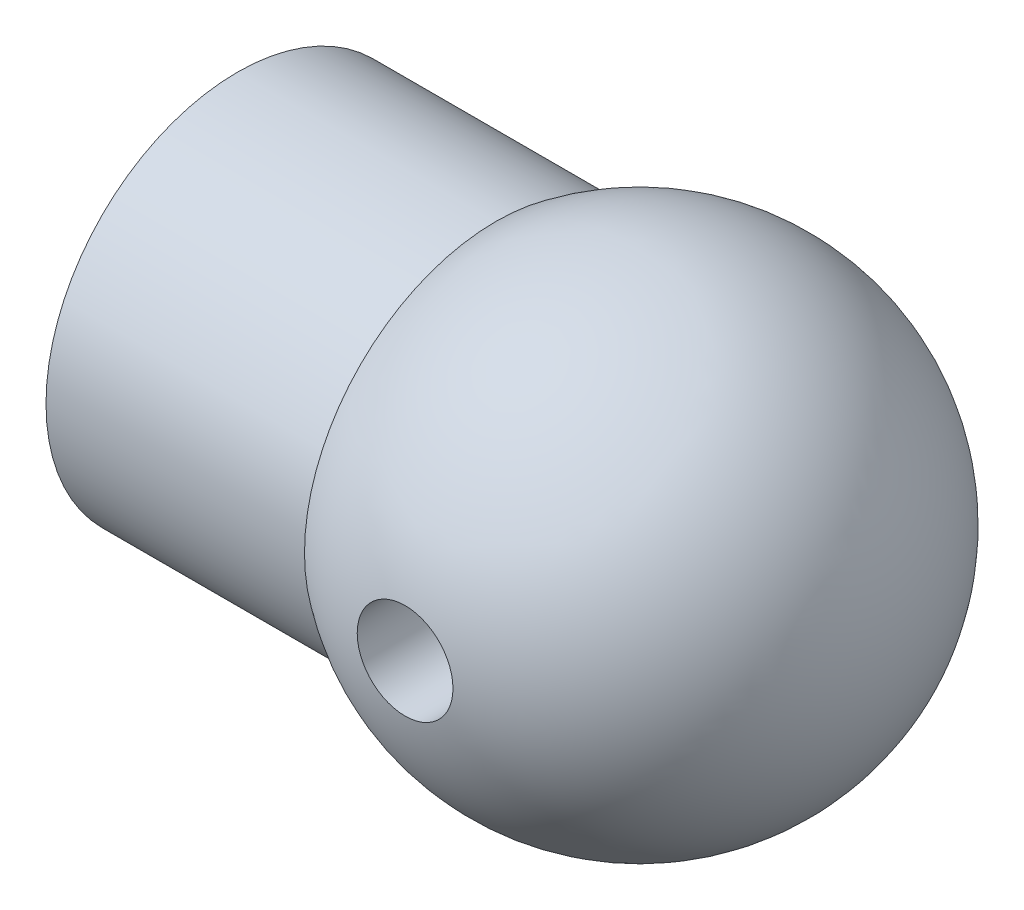
SolidWorks part; units mm, degrees
ref_plane "前视基准面" through (0, 0, 0) normal (0, 0, 1) x (1, 0, 0)
ref_plane "上视基准面" through (0, 0, 0) normal (0, 1, 0) x (1, 0, 0)
ref_plane "右视基准面" through (0, 0, 0) normal (1, 0, 0) x (0, 0, -1)
sketch "草图1" plane through (0, 0, 0) normal (0, 0, 1) x (1, 0, 0)
  line L0 (0, 0) -> (67, 0) construction
  line L1 (0, 0) -> (0, 20)
  line L2 (0, 20) -> (27, 20)
  line L3 (0, 0) -> (67, 0)
  arc A1 (67, 0) -> (27, 20) centre (42, 0) ccw
  point P6 (70, 0)
  dimension "D1" = 20
  dimension "D3" = 25
  dimension "D2" = 27
revolve "旋转1" add sketch "草图1" angle 360 about L0
sketch "草图3" plane through (0, 0, 0) normal (0, 0, 1) x (1, 0, 0)
  circle A0 centre (42, 0) radius 5
  dimension "D1" = 10
extrude "切除-拉伸1" cut sketch "草图3" against normal through all both and the other way through all
